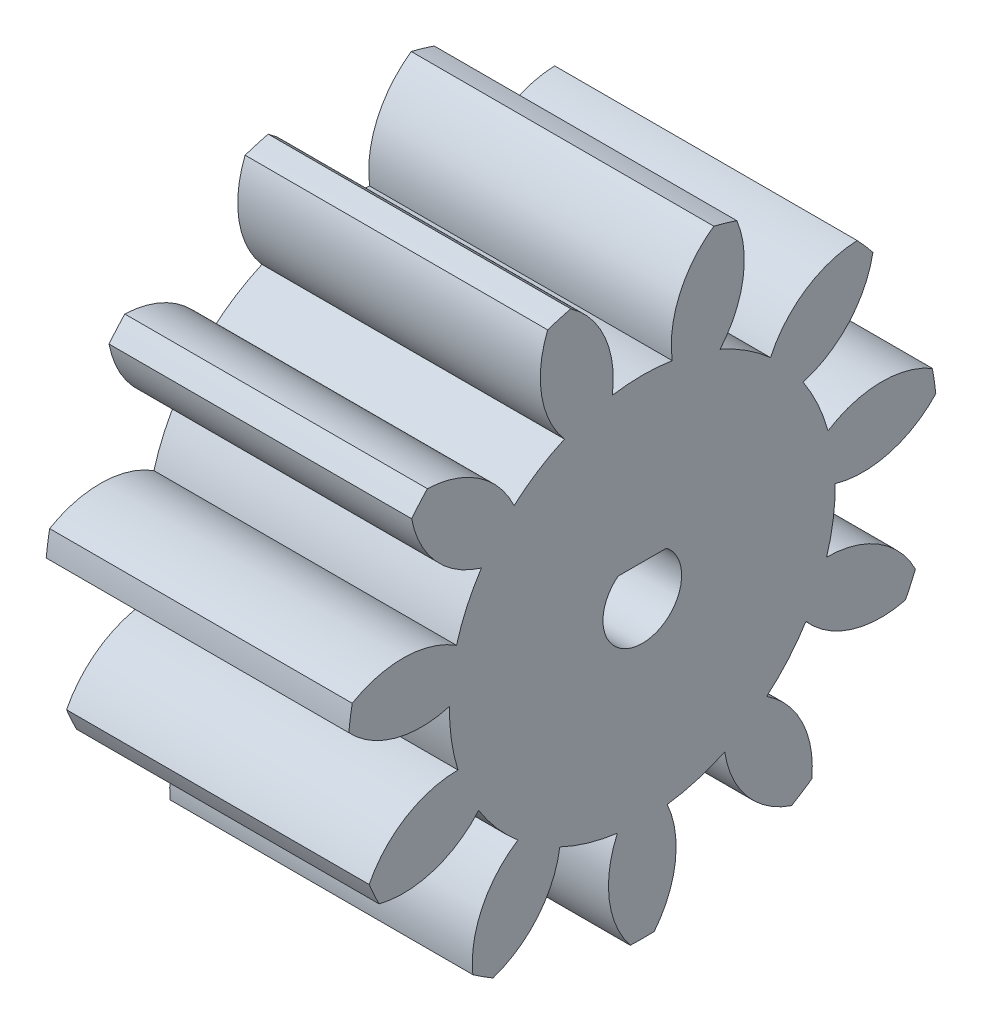
SolidWorks part; units mm, degrees
ref_plane "Plane1" through (0, 0, 0) normal (0, 0, 1) x (1, 0, 0)
ref_plane "Plane2" through (0, 0, 0) normal (0, 1, 0) x (1, 0, 0)
ref_plane "Plane3" through (0, 0, 0) normal (1, 0, 0) x (0, 0, -1)
other "Configuration Table"
sketch "HoldingSke" plane through (0, 0, 0) normal (0, 1, 0) x (1, 0, 0)
  line L0 (0, 0) -> (0.3272, -0.0636)
  line L1 (-15, 0) -> (100, 0) construction
  line L2 (0, 0) -> (-2.1039, 2.3779)
  line L3 (0, 0) -> (-11.863, 4.5341)
  line L4 (0, 0) -> (8.4773, 1.6478)
  line L5 (0, 0) -> (-46.8476, -17.4728)
  line L6 (0, 0) -> (-16.5793, -11.1861)
  line L7 (-2.1039, 2.3779) -> (8.6586, 51.2059)
  line L8 (-76.2, 54.61) -> (-75.3, 54.61)
  line L9 (-67.7845, 28.3722) -> (-49.3413, 33.142)
  line L10 (-76.2, 71.12) -> (104.1128, 71.12)
  line L11 (0, 0) -> (-20, 0)
  line L12 (-76.2, 101.6) -> (-76.093, 101.6)
  line L13 (24.9733, 27.94) -> (52.9518, 28.4284)
  line L14 (24.9733, 27.94) -> (24.9743, 27.94)
  line L15 (24.9733, 27.94) -> (100.4006, 29.5858)
  line L16 (-63.627, -3) -> (-12.827, -3)
  circle A0 centre (0, 0) radius 2.5
  circle A1 centre (0, 0) radius 12.749
  circle A2 centre (0, 0) radius 37.5
  circle A3 centre (0, 0) radius 2.5
  dimension "MHD" = 25.498
  dimension "Hub_dia" = 75
  dimension "Bore" = 5
  dimension "MBD" = 5
  dimension "Num_teeth" = 11
  dimension "Pitch" = 0.3333
  dimension "Overall_len" = 50
  dimension "Show_teeth" = 11
  dimension "Thickness" = 20
  dimension "OAL" = 50.0001
  dimension "T_dim" = 0.9
  dimension "Ap" = 14.5
  dimension "H" = 19.05
  dimension "Pitch_radius" = 180.3128
  dimension "Width" = 20
  dimension "Backlash" = 0.107
  dimension "Addendum_fac" = 1
  dimension "Dedendum_fac" = 1.25
  dimension "Clearance_fac" = 0.25
  dimension "Dedendum_add" = 0.001
  dimension "Module" = 3
sketch "BasProSke" plane through (0, 0, 0) normal (0, 1, 0) x (1, 0, 0)
  line L0 (-10, 0) -> (60, 0) construction
  line L1 (0, 0) -> (0, 19.5)
  line L2 (0, 0) -> (20, 0)
  line L3 (20, 0) -> (20, 19.5)
  line L4 (20, 19.5) -> (0, 19.5)
  dimension "Thickness" = 20
  dimension "Diameter" = 39
revolve "Base-Revolve" add sketch "BasProSke" angle 360 about L0
sketch "TooCutSke" plane through (0, 0, 0) normal (1, 0, 0) x (0, 0, -1)
  line L1 (0, 0) -> (0, 107) construction
  line L2 (0, 0) -> (-2.5351, 16.3041) construction
  line L3 (0, 0) -> (-9.2171, 31.3905) construction
  line L4 (-2.5351, 16.3041) -> (-4.6085, 15.6953) construction
  arc A0 (1.9813, 12.5941) -> (-1.9813, 12.5941) centre (0, 0) ccw
  arc A1 (4.7548, 18.9376) -> (-4.7548, 18.9376) centre (0, 0) ccw
  circle A2 centre (0, 0) radius 16.5 construction
  circle A3 centre (0, 0) radius 15.9744 construction
  arc A4 (-1.9813, 12.5941) -> (-4.7548, 18.9376) centre (-8.5167, 13.5147) ccw
  arc A5 (4.7548, 18.9376) -> (1.9813, 12.5941) centre (8.5167, 13.5147) ccw
  dimension "Root_dia" = 25.498
  dimension "Overcut_dia" = 39.0508
  dimension "Pitch_dia" = 33
  dimension "Base_dia" = 31.9489
  dimension "Flank_rad" = 6.6
  dimension "Half_ang" = 16.364
  dimension "Half_CT" = 2.1609
extrude "ToothCut" cut sketch "TooCutSke" along normal through all
fillet "Breaks" [suppressed] radius 0.06
fillet "RootFillets" [suppressed] radius 0.751
pattern_circular "TeethCuts" count 11 over 360 about axis through (0, 0, 0) along (1, 0, 0) of "ToothCut", "RootFillets", "Breaks"
sketch "HubNeaOneSke" plane through (0, 0, 0) normal (-1, 0, 0) x (0, 0, 1)
  circle A0 centre (0, 0) radius 12.749
  dimension "Diameter" = 25.498
extrude "HubNearOne" [suppressed] add sketch "HubNeaOneSke" along normal blind 30.0001
sketch "HubNeaBotSke" plane through (0, 0, 0) normal (-1, 0, 0) x (0, 0, 1)
  circle A0 centre (0, 0) radius 12.749
  dimension "Diameter" = 25.498
extrude "HubNearBoth" [suppressed] add sketch "HubNeaBotSke" along normal blind 15
ref_plane "FarPln" through (20, 0, 0) normal (1, 0, 0) x (0, 0, -1)
sketch "HubFarSke" plane through (20, 0, 0) normal (1, 0, 0) x (0, 0, -1)
  circle A0 centre (0, 0) radius 12.749
  dimension "Diameter" = 25.498
extrude "HubFar" [suppressed] add sketch "HubFarSke" along normal blind 15
sketch "BorSke" plane through (0, 0, 0) normal (1, 0, 0) x (0, 0, -1)
  circle A0 centre (0, 0) radius 2.5
  dimension "Diameter" = 5
extrude "Bore" cut sketch "BorSke" along normal mid plane 100.0001
sketch "KeySke" plane through (0, 0, 0) normal (1, 0, 0) x (0, 0, -1)
  line L0 (-1, 0) -> (-1, 3.4)
  line L1 (-1, 3.4) -> (1, 3.4)
  line L2 (1, 3.4) -> (1, 0)
  line L3 (0, 0) -> (0, 34) construction
  line L4 (-1, 0) -> (1, 0)
  dimension "Offset" = 3.4
extrude "Keyway" [suppressed] cut sketch "KeySke" along normal mid plane 100.0001
pattern_circular "Keyway2" [suppressed] count 2 every 90 about axis through (-10, 0, 0) along (1, 0, 0)
sketch "Sketch1" plane through (20, 0, 0) normal (1, 0, 0) x (0, 0, -1)
  circle A0 centre (0, 0) radius 2.6
  dimension "D1" = 5.2
extrude "Cut-Extrude1" cut sketch "Sketch1" against normal through all
sketch "Sketch2" plane through (20, 0, 0) normal (1, 0, 0) x (0, 0, -1)
  line L0 (-1.6003, 2.0492) -> (1.5997, 2.0496)
  arc A0 (1.5997, 2.0496) -> (-1.6003, 2.0492) centre (0, 0) ccw
  circle A1 centre (0, 0) radius 2.6 construction
  point P5 (1.2454, 2.2823)
  point P6 (-1.5997, 2.0496)
  dimension "D1" = 3.2
extrude "Boss-Extrude1" add sketch "Sketch2" against normal through all
equation "' \"Module@HoldingSke\" = 6.35"
equation "' \"Num_teeth@HoldingSke\" = 12"
equation "' \"Ap@HoldingSke\" =  20"
equation "' \"Ap@HoldingSke\" = 20"
equation "' \"Width@HoldingSke\" = 0.5 * 25.4"
equation "' \"Hub_dia@HoldingSke\"= 1 * 25.4"
equation "' \"Hub_dia@HoldingSke\" = 1 * 25.4"
equation "' \"Overall_len@HoldingSke\" = 1.0 * 25.4"
equation "' \"Bore@HoldingSke\" = 0.75 * 25.4"
equation "' \"T_dim@HoldingSke\" = 0.1 * 25.4"
equation "' \"Width@KeySke\" = 0.25 * 25.4"
equation "' \"Show_teeth@HoldingSke\" = 13"
equation "' \"Backlash@HoldingSke\" = 0.009 * 25.4"
equation "' \"Addendum_fac@HoldingSke\" = 1.0"
equation "' \"Dedendum_fac@HoldingSke\" = 1.25"
equation "' \"Dedendum_add@HoldingSke\" = 0.00005 * 25.4"
equation "' \"Clearance_fac@HoldingSke\" = 0.25"
equation "\"Pitch@HoldingSke\" = 1 / \"Module@HoldingSke\""
equation "\"Overcut_dia@TooCutSke\" = (\"Num_teeth@HoldingSke\" + 2 * \"Addendum_fac@HoldingSke\") / \"Pitch@HoldingSke\" + 0.002 * 25.4"
equation "\"Pitch_dia@TooCutSke\" = \"Num_teeth@HoldingSke\" / \"Pitch@HoldingSke\""
equation "\"Base_dia@TooCutSke\" = \"Num_teeth@HoldingSke\" / \"Pitch@HoldingSke\" * cos((\"Ap@HoldingSke\"  * 3.14159265 / 180))"
equation "\"Root_dia@TooCutSke\" = (\"Num_teeth@HoldingSke\" + 2) / \"Pitch@HoldingSke\" - 2 * (\"Addendum_fac@HoldingSke\" + \"Dedendum_fac@HoldingSke\") / \"Pitch@HoldingSke\" - \"Dedendum_add@HoldingSke\" * 2"
equation "\"Half_ang@TooCutSke\" = 180 / \"Num_teeth@HoldingSke\""
equation "\"Half_CT@TooCutSke\" = \"Num_teeth@HoldingSke\" / \"Pitch@HoldingSke\" * sin((3.14159265 / 2 / \"Num_teeth@HoldingSke\")) / 2 - 7 * \"Backlash@HoldingSke\" / 4"
equation "\"Flank_rad@TooCutSke\" = \"Num_teeth@HoldingSke\" / \"Pitch@HoldingSke\" / 5"
equation "\"Radius@RootFillets\" = \"Clearance_fac@HoldingSke\" / \"Pitch@HoldingSke\" + \"Dedendum_add@HoldingSke\""
equation "\"Break_rad@Breaks\" = 0.02 / \"Pitch@HoldingSke\""
equation "\"Thickness@HoldingSke\" = \"Width@HoldingSke\""
equation "\"OAL@HoldingSke\" = \"Thickness@HoldingSke\""
equation "\"MHD@HoldingSke\" = (\"Num_teeth@HoldingSke\" + 2) / \"Pitch@HoldingSke\" - 2 * (\"Addendum_fac@HoldingSke\" + \"Dedendum_fac@HoldingSke\")  / \"Pitch@HoldingSke\" - \"Dedendum_add@HoldingSke\" * 2"
equation "\"MBD@HoldingSke\" = (\"Num_teeth@HoldingSke\" + 2) / \"Pitch@HoldingSke\" - 2 * (\"Addendum_fac@HoldingSke\" + \"Dedendum_fac@HoldingSke\")  / \"Pitch@HoldingSke\" - \"Dedendum_add@HoldingSke\" * 2 - 0.002 * 25.4"
equation "\"MHD@HoldingSke\" = ((sgn( \"MHD@HoldingSke\" - \"Hub_dia@HoldingSke\" )-1)*( \"MHD@HoldingSke\" - \"Hub_dia@HoldingSke\" ))/-2+ \"Hub_dia@HoldingSke\""
equation "\"MBD@HoldingSke\" = ((sgn( \"MBD@HoldingSke\" - \"Bore@HoldingSke\" )-1)*( \"MBD@HoldingSke\" - \"Bore@HoldingSke\" ))/-2+ \"Bore@HoldingSke\""
equation "\"OAL@HoldingSke\" = ((sgn( \"OAL@HoldingSke\" - \"Overall_len@HoldingSke\" )+1)*( \"OAL@HoldingSke\" - \"Overall_len@HoldingSke\" ))/2 + \"Overall_len@HoldingSke\" + 0.000002 * 25.4"
equation "\"Num_teeth@TeethCuts\" = int( \"Show_teeth@HoldingSke\" ) + 1"
equation "\"Num_teeth@TeethCuts\" = ((sgn( \"Num_teeth@TeethCuts\" - \"Num_teeth@HoldingSke\" )-1)*( \"Num_teeth@TeethCuts\" - \"Num_teeth@HoldingSke\" ))/-2+ \"Num_teeth@HoldingSke\""
equation "\"Num_teeth@TeethCuts\" = ((sgn( \"Num_teeth@TeethCuts\" - 2.0)+1)*( \"Num_teeth@TeethCuts\" - 2.0))/2 +2.0"
equation "\"Angle@TeethCuts\" = 360.0 / \"Num_teeth@HoldingSke\""
equation "\"Diameter@BasProSke\" = (\"Num_teeth@HoldingSke\" + 2 * \"Addendum_fac@HoldingSke\") / \"Pitch@HoldingSke\""
equation "\"Thickness@BasProSke\"  = \"Thickness@HoldingSke\""
equation "' \"Fillet_rad@BasProSke\" =  \"Thickness@HoldingSke\" * 0.05"
equation "' \"Fillet_rad@BasProSke\" = \"Thickness@HoldingSke\" * 0.05"
equation "\"MHD@HoldingSke\" = ((sgn( \"MHD@HoldingSke\" - \"Root_dia@TooCutSke\" )-1)*( \"MHD@HoldingSke\" - \"Root_dia@TooCutSke\" ))/-2+ \"Root_dia@TooCutSke\""
equation "\"Diameter@HubNeaOneSke\" = \"MHD@HoldingSke\""
equation "\"Length@HubNearOne\" = \"OAL@HoldingSke\" - \"Thickness@BasProSke\""
equation "\"Diameter@HubNeaBotSke\" = \"MHD@HoldingSke\""
equation "\"Length@HubNearBoth\" = ( \"OAL@HoldingSke\" - \"Thickness@BasProSke\" ) / 2.0"
equation "\"Thickness@FarPln\" = \"Thickness@BasProSke\""
equation "\"Diameter@HubFarSke\" = \"MHD@HoldingSke\""
equation "\"Length@HubFar\" = ( \"OAL@HoldingSke\" - \"Thickness@BasProSke\" ) / 2.0"
equation "\"Diameter@BorSke\" = \"MBD@HoldingSke\""
equation "\"D1@Bore\" = \"OAL@HoldingSke\" * 2.0"
equation "\"D1@Keyway\" = \"OAL@HoldingSke\" * 2.0"
equation "\"Offset@KeySke\" = \"T_dim@HoldingSke\" + \"MBD@HoldingSke\" / 2.0"
